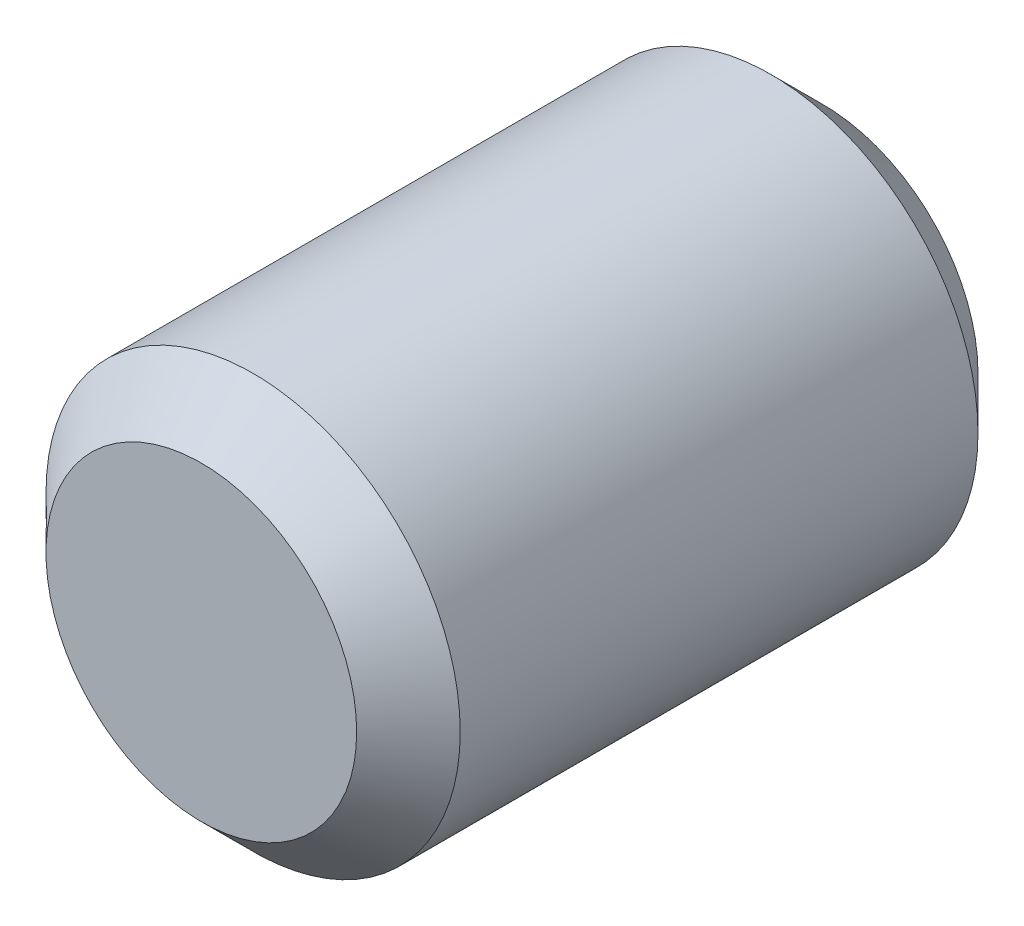
SolidWorks part; units mm, degrees
ref_plane "Ön Düzlem" through (0, 0, 0) normal (0, 0, 1) x (1, 0, 0)
ref_plane "Üst Düzlem" through (0, 0, 0) normal (0, 1, 0) x (1, 0, 0)
ref_plane "Sağ Düzlem" through (0, 0, 0) normal (1, 0, 0) x (0, 0, -1)
sketch "Çizim1" plane through (0, 0, 0) normal (0, 0, 1) x (1, 0, 0)
  circle A0 centre (0, 0) radius 2
  dimension "D1" = 4
extrude "Yükseklik-Ekstrüzyon1" add sketch "Çizim1" along normal mid plane 6
chamfer "Pah1" distance 0.5 angle 45 2 edges at (2, 0, -3) (2, 0, 3)
